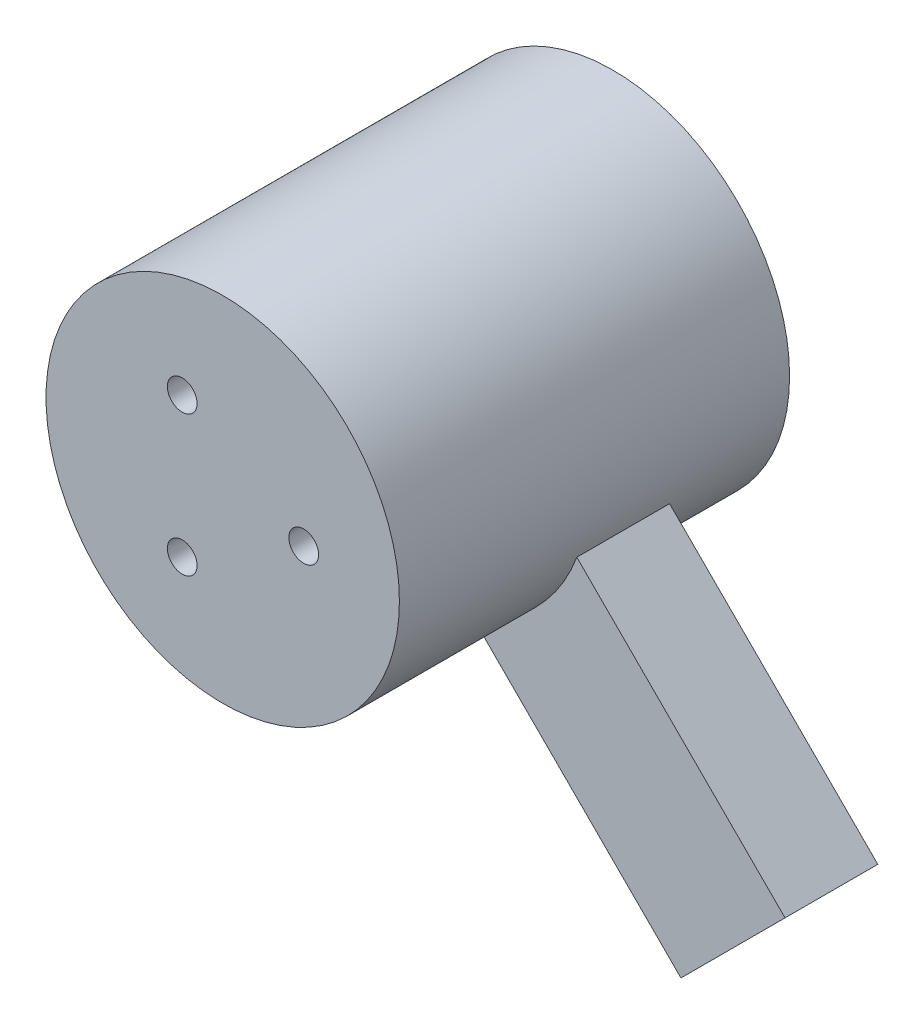
SolidWorks part; units mm, degrees
ref_plane "前视基准面" through (0, 0, 0) normal (0, 0, 1) x (1, 0, 0)
ref_plane "上视基准面" through (0, 0, 0) normal (0, 1, 0) x (1, 0, 0)
ref_plane "右视基准面" through (0, 0, 0) normal (1, 0, 0) x (0, 0, -1)
sketch "草图1" plane through (0, 0, 0) normal (0, 0, 1) x (1, 0, 0)
  line L0 (-0.6584, 0) -> (-50000.6584, 0) construction
  line L1 (0, 0) -> (0, 50000) construction
  circle A0 centre (0, 0) radius 12
  circle A1 centre (-8, 0) radius 1.5
  circle A2 centre (8, 0) radius 1.5
  circle A3 centre (0, 8) radius 1.5
  circle A4 centre (0, -8) radius 1.5
  dimension "D1" = 24
  dimension "D2" = 3
  dimension "D4" = 3
  dimension "D3" = 16
  dimension "D5" = 16
extrude "凸台-拉伸1" add sketch "草图1" along normal blind 28
sketch "草图2" plane through (0, 0, 28) normal (0, 0, 1) x (1, 0, 0)
  circle A0 centre (0, 0) radius 20
  dimension "D1" = 40
extrude "凸台-拉伸2" add sketch "草图2" against normal blind 11
sketch "草图3" plane through (0, 0, 0) normal (0, 0, -1) x (-1, 0, 0)
  line L0 (-5, -10.9087) -> (-5, -30.9087) construction
  line L1 (-5, -30.9087) -> (5, -30.9087) construction
  line L2 (5, -30.9087) -> (5, -10.9087) construction
  line L3 (0, 0) -> (-19134.1716, -46193.9766) construction
  line L4 (-18.3202, -25.3913) -> (-25.3913, -18.3202)
  line L5 (-25.3913, -18.3202) -> (-11.2492, -4.1781)
  line L6 (-4.1781, -11.2492) -> (-18.3202, -25.3913)
  circle A0 centre (0, 0) radius 12 construction
  circle A1 centre (0, 0) radius 12
  circle M3 centre (0, 0) radius 12
  dimension "D4" = 24
  dimension "D1" = 5
  dimension "D2" = 5
  dimension "D3" = 20
  dimension "D5" = 22.5
extrude "凸台-拉伸3" add sketch "草图3" against normal blind 6.3 from offset 7.4 contours L1 L2 L0 M3 offset against normal yes
sketch "草图4" plane through (0, 0, 17) normal (0, 0, -1) x (-1, 0, 0)
  circle A0 centre (0, 0) radius 12
  circle A1 centre (0, 0) radius 20
  circle A2 centre (0, 0) radius 20
  dimension "D1" = 0
extrude "切除-拉伸1" cut sketch "草图4" against normal blind 39
sketch "草图5" plane through (0, 0, 28) normal (0, 0, 1) x (1, 0, 0)
  circle A1 centre (0, 0) radius 12
  circle A2 centre (0, 0) radius 12
  dimension "D1" = 0
extrude "切除-拉伸2" cut sketch "草图5" against normal blind 1.5
sketch "草图6" plane through (0, 0, 26.5) normal (0, 0, 1) x (1, 0, 0)
  circle A0 centre (0, 0) radius 5.5 construction
  circle A1 centre (5.5, 0) radius 1.01
  circle A2 centre (-2.75, -4.7631) radius 1.01
  circle A3 centre (-2.75, 4.7631) radius 1.01
  point P5 (-2.9748, 4.6261)
  point P6 (-2.8204, -4.8448)
  point P7 (-2.7465, -4.7652)
  point P12 (0, 0)
  dimension "D1" = 11
  dimension "D2" = 2.02
  dimension "D3" = 3
extrude "切除-拉伸3" cut sketch "草图6" against normal blind 1.5
